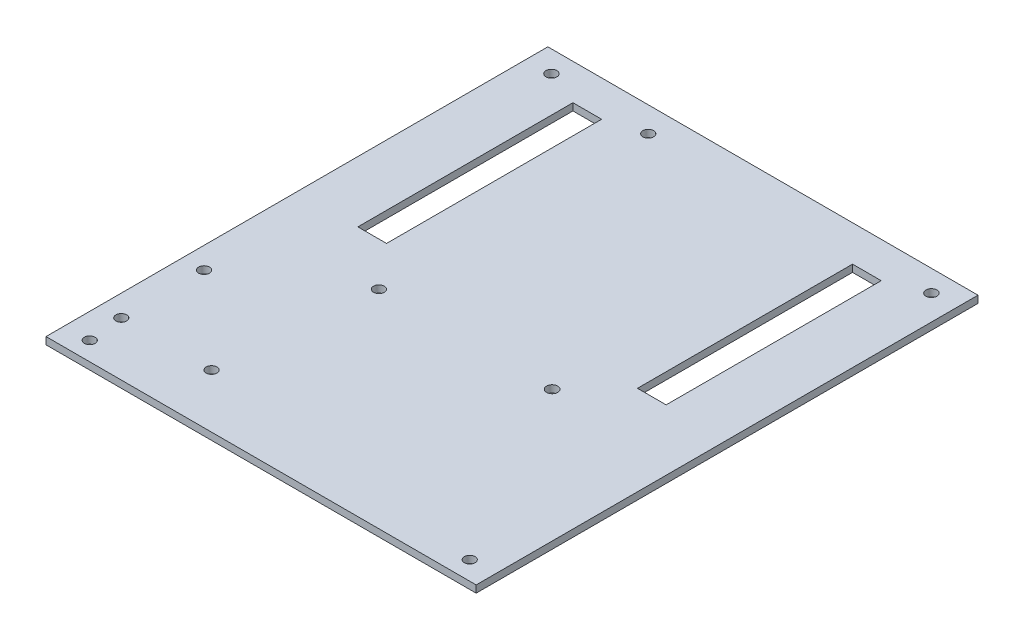
SolidWorks part; units mm, degrees
ref_plane "Front Plane" through (0, 0, 0) normal (0, 0, 1) x (1, 0, 0)
ref_plane "Top Plane" through (0, 0, 0) normal (0, 1, 0) x (1, 0, 0)
ref_plane "Right Plane" through (0, 0, 0) normal (1, 0, 0) x (0, 0, -1)
sketch "Sketch1" plane through (0, 0, 0) normal (0, 1, 0) x (1, 0, 0)
  line L1 (60, -70) -> (-60, -70)
  line L2 (60, -70) -> (60, 70)
  line L3 (60, 70) -> (-60, 70)
  line L4 (-60, -70) -> (-60, 70)
  line L5 (60, -70) -> (-60, 70) construction
  line L6 (60, 70) -> (-60, -70) construction
  point P0 (0, 0)
  dimension "D1" = 140
  dimension "D2" = 120
extrude "Boss-Extrude1" add sketch "Sketch1" along normal blind 2
sketch "Sketch2" plane through (0, 2, 0) normal (0, 1, 0) x (1, 0, 0)
  line L0 (0, 0) -> (0, 70) construction
  line L1 (60, 70) -> (-60, 70) construction
  line L2 (0, 0) -> (-60, 0) construction
  line L3 (-60, 70) -> (-60, -70) construction
  line L4 (-60, -70) -> (60, -70) construction
  circle A0 centre (-53, 64) radius 1.525
  circle A1 centre (-53, -64.8) radius 1.5
  circle A2 centre (53, 64) radius 1.525
  circle A3 centre (53, -64.8) radius 1.5
  dimension "D1" = 3.05
  dimension "D2" = 6
  dimension "D3" = 7
  dimension "D4" = 3
  dimension "D5" = 5.2
  dimension "D6" = 7
extrude "Cut-Extrude1" cut sketch "Sketch2" against normal blind 2
sketch "Sketch4" plane through (0, 2, 0) normal (0, 1, 0) x (1, 0, 0)
  line L0 (60, 70) -> (-60, 70) construction
  line L1 (-60, 70) -> (-60, -70) construction
  line L2 (0, 0) -> (0, 70) construction
  line L3 (-35, 60) -> (-43, 60)
  line L4 (-35, 60) -> (-35, 0)
  line L5 (-35, 0) -> (-43, 0)
  line L6 (-43, 60) -> (-43, 0)
  line L7 (-35, 60) -> (-43, 0) construction
  line L8 (-35, 0) -> (-43, 60) construction
  line L9 (35, 0) -> (43, 0)
  line L10 (35, 60) -> (35, 0)
  line L11 (43, 60) -> (43, 0)
  line L12 (35, 60) -> (43, 60)
  circle A0 centre (-25, 63) radius 1.5
  circle A1 centre (-25, -12.13) radius 1.5
  circle A2 centre (23.33, -12.13) radius 1.55
  point P10 (-39, 30)
  dimension "D1" = 3
  dimension "D2" = 3
  dimension "D4" = 7
  dimension "D5" = 35
  dimension "D6" = 35
  dimension "D7" = 3.1
  dimension "D9" = 82.13
  dimension "D3" = 75.13
  dimension "D8" = 48.33
  dimension "D10" = 8
  dimension "D11" = 10
  dimension "D12" = 60
  dimension "D13" = 17
extrude "Cut-Extrude2" cut sketch "Sketch4" against normal through all
sketch "Sketch5" plane through (0, 2, 0) normal (0, 1, 0) x (1, 0, 0)
  line L0 (-60, 70) -> (-60, -70) construction
  line L1 (-60, -70) -> (60, -70) construction
  circle A0 centre (-54, -55) radius 1.5
  circle A1 centre (-28.82, -55) radius 1.5
  circle A2 centre (-54, -31.9) radius 1.5
  dimension "D1" = 3
  dimension "D2" = 3
  dimension "D4" = 3
  dimension "D8" = 15
  dimension "D9" = 15
  dimension "D3" = 25.18
  dimension "D5" = 23.1
  dimension "D6" = 6
  dimension "D7" = 6
extrude "Cut-Extrude3" cut sketch "Sketch5" against normal through all
